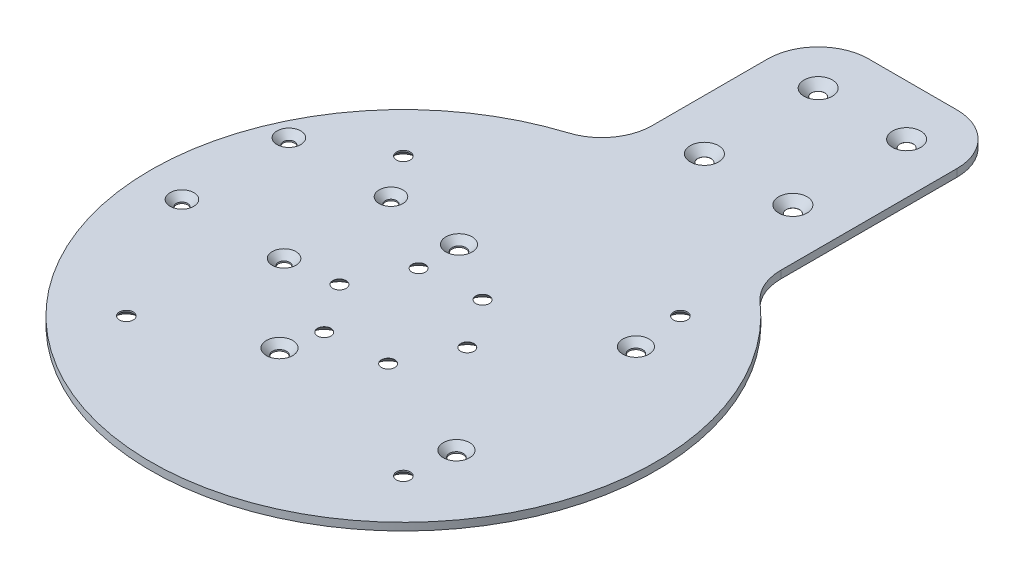
SolidWorks part; units mm, degrees
other "Markup1"
sketch "Sketch22" plane through (-100, 5, 100) normal (0, 1, 0) x (-1, 0, 0)
other "Markup2"
sketch "Sketch23" plane through (-100, 0, -180.1) normal (0, -1, 0) x (1, 0, 0)
material "6061-T6 (SS)"
ref_plane "Front Plane" through (0, 0, 0) normal (0, 0, 1) x (1, 0, 0)
ref_plane "Top Plane" through (0, 0, 0) normal (0, 1, 0) x (1, 0, 0)
ref_plane "Right Plane" through (0, 0, 0) normal (1, 0, 0) x (0, 0, -1)
sketch "Sketch1" plane through (0, 0, 0) normal (0, 1, 0) x (1, 0, 0)
  circle A0 centre (0, 0) radius 100
  dimension "D1" = 200
extrude "Boss-Extrude1" add sketch "Sketch1" along normal blind 3
sketch "Sketch2" plane through (0, 0, 0) normal (0, -1, 0) x (1, 0, 0)
  circle A0 centre (0, 0) radius 105
  dimension "D1" = 210
sketch "Sketch3" plane through (0, 0, 0) normal (0, 0, 1) x (1, 0, 0)
  line L1 (100, 3) -> (-100, 3) construction
  circle A0 centre (105, 4) radius 3.25
  dimension "D1" = 6.5
  dimension "D2" = 1
  dimension "D3" = 105
sweep "Cut-Sweep1" [suppressed] cut profiles "Sketch3" path "Sketch2"
sketch "Sketch4" plane through (0, 0, 0) normal (0, -1, 0) x (1, 0, 0)
  circle A0 centre (0, 0) radius 100 construction
  circle A1 centre (23.4262, -1.8614) radius 2.6
  circle A3 centre (10.1011, -21.2183) radius 2.6
  circle A5 centre (-13.3251, -19.357) radius 2.6
  circle A7 centre (-23.4262, 1.8614) radius 2.6
  circle A9 centre (-10.1011, 21.2183) radius 2.6
  circle A11 centre (0, 0) radius 95 construction
  circle A13 centre (0, 0) radius 110 construction
  circle A14 centre (0, 0) radius 29.5 construction
  circle A18 centre (13.3251, 19.357) radius 2.6
  point P14 (0, 0)
  dimension "D1" = 59
  dimension "D2" = 6
  dimension "D4" = 190
  dimension "D5" = 220
  dimension "D3" = 23.5
hole_wizard "CSK for M5 SFHCS1" positions "Sketch5" profile "Sketch6" countersink size "M5" standard "ANSI Metric" end condition through all
sketch "Sketch5" plane through (0, 0, 0) normal (0, -1, 0) x (-1, 0, 0)
  point P0 (13.3251, 19.357)
  point P3 (-10.1011, 21.2183)
  point P6 (-23.4262, 1.8614)
  point P9 (-13.3251, -19.357)
  point P12 (10.1011, -21.2183)
  point P15 (23.4262, -1.8614)
sketch "Sketch6" plane through (-13.3251, 0, -19.357) normal (1, 0, 0) x (0, 0, -1)
  line L0 (0, 0) -> (0, 3)
  line L1 (0, 3) -> (2.65, 3)
  line L2 (2.65, 3) -> (2.65, 2.95)
  line L3 (2.65, 2.95) -> (5.6, 0)
  line L5 (5.6, 0) -> (0, 0)
  line L6 (-2.65, 2.95) -> (-5.6, 0) construction
  line L11 (0, -6.35) -> (0, 107.95) construction
  dimension "Thru Hole Dia." = 5.3
  dimension "Thru Hole Depth" = 3
  dimension "Near C'Sink Dia." = 11.2
  dimension "Near C'Sink Angle" = 90
sketch "Sketch7" plane through (0, 0, 0) normal (0, -1, 0) x (1, 0, 0)
  line L4 (-16, -98.7117) -> (-16, -180.1)
  line L5 (-16, -180.1) -> (59, -180.1)
  line L6 (59, -180.1) -> (59, -80.7403)
  arc A0 (-16, -98.7117) -> (59, -80.7403) centre (0, 0) ccw
  circle A1 centre (0, 0) radius 110 construction
  circle A2 centre (0, 0) radius 100 construction
  dimension "D1" = 75
  dimension "D2" = 16
  dimension "D3" = 180.1
extrude "Boss-Extrude2" add sketch "Sketch7" against normal blind 3
fillet "Fillet1" radius 20 4 edges at (-16, 1.5, -180.1) (59, 1.5, -180.1) (59, 1.5, -80.7403) (-16, 1.5, -98.7117)
sketch "Sketch11" plane through (0, 3, 0) normal (0, -1, 0) x (1, 0, 0)
  line L0 (59, -160.1) -> (59, -90.3272) construction
  line L1 (4, -180.1) -> (39, -180.1) construction
  circle A0 centre (4, -115.1) radius 3.1
  circle A1 centre (39, -115.1) radius 3.1
  circle A2 centre (39, -160.1) radius 3.1
  circle A3 centre (4, -160.1) radius 3.1
  dimension "D1" = 6.2
  dimension "D2" = 6.2
  dimension "D3" = 6.2
  dimension "D4" = 6.2
  dimension "D5" = 35
  dimension "D6" = 45
  dimension "D7" = 20
  dimension "D8" = 20
hole_wizard "CSK for M5 SFHCS2" positions "Sketch12" profile "Sketch14" countersink size "M5" standard "ANSI Metric" end condition through all
sketch "Sketch12" plane through (0, 3, 0) normal (0, 1, 0) x (1, 0, 0)
  point P0 (39, 160.1)
  point P3 (4, 160.1)
  point P6 (39, 115.1)
  point P9 (4, 115.1)
sketch "Sketch14" plane through (39, 3, -160.1) normal (1, 0, 0) x (0, 0, 1)
  line L0 (0, 0) -> (0, 3)
  line L1 (0, 3) -> (2.65, 3)
  line L2 (2.65, 3) -> (2.65, 2.95)
  line L3 (2.65, 2.95) -> (5.6, 0)
  line L5 (5.6, 0) -> (0, 0)
  line L6 (-2.65, 2.95) -> (-5.6, 0) construction
  line L11 (0, -6.35) -> (0, 107.95) construction
  dimension "Thru Hole Dia." = 5.3
  dimension "Thru Hole Depth" = 3
  dimension "Near C'Sink Dia." = 11.2
  dimension "Near C'Sink Angle" = 90
sketch "Sketch15" plane through (0, 0, 0) normal (0, -1, 0) x (1, 0, 0)
  line L0 (0, 0) -> (-54.8008, 54.8008) construction
  line L1 (0, 77.5) -> (0, 0) construction
  circle A0 centre (56.5, -35.5) radius 2.5
  circle A1 centre (56.5, 35.5) radius 2.5
  circle A2 centre (-13.5, 35.5) radius 2.5
  circle A3 centre (-13.5, -35.5) radius 2.5
  circle A4 centre (-43.3, -38.4) radius 2
  circle A5 centre (-43.3, 3.9) radius 2
  circle A6 centre (-83.7, -38.4) radius 2
  circle A7 centre (-83.7, 3.9) radius 2
  circle A8 centre (0, 0) radius 70 construction
  arc A9 (65.8333, -75.2727) -> (-30, -95.3939) centre (0, 0) ccw construction
  circle A10 centre (0, 0) radius 77.5 construction
  circle A12 centre (-54.8008, 54.8008) radius 2.5
  circle A13 centre (54.8008, 54.8008) radius 2.5
  circle A14 centre (54.8008, -54.8008) radius 2.5
  circle A15 centre (-54.8008, -54.8008) radius 2.5
  point P35 (0, 0)
  dimension "D1" = 30
  dimension "D2" = 7.5
  dimension "D3" = 5
  dimension "D4" = 45
  dimension "D5" = 4
hole_wizard "CSK for M5 Flat Head Machine Screw2" positions "Sketch16" profile "Sketch17" countersink size "M5" standard "ANSI Metric" end condition through all
sketch "Sketch16" plane through (0, 3, 0) normal (0, 1, 0) x (1, 0, 0)
  circle A2 centre (-83.7, -3.9) radius 2
  circle A3 centre (-83.7, -3.9) radius 2
  circle A6 centre (-83.7, 38.4) radius 2
  circle A7 centre (-83.7, 38.4) radius 2
  circle A10 centre (-43.3, -3.9) radius 2
  circle A11 centre (-43.3, -3.9) radius 2
  circle A14 centre (-43.3, 38.4) radius 2
  circle A15 centre (-43.3, 38.4) radius 2
  circle A18 centre (-13.5, 35.5) radius 2.5
  circle A19 centre (-13.5, 35.5) radius 2.5
  circle A22 centre (-13.5, -35.5) radius 2.5
  circle A23 centre (-13.5, -35.5) radius 2.5
  circle A26 centre (56.5, -35.5) radius 2.5
  circle A27 centre (56.5, -35.5) radius 2.5
  circle A30 centre (56.5, 35.5) radius 2.5
  circle A31 centre (56.5, 35.5) radius 2.5
  point P33 (-13.5, 35.5)
  point P40 (-13.5, -35.5)
  point P47 (56.5, -35.5)
  point P54 (56.5, 35.5)
  dimension "D1" = 0
  dimension "D2" = 0
  dimension "D3" = 0
  dimension "D4" = 0
  dimension "D5" = 0
  dimension "D6" = 0
  dimension "D7" = 0
  dimension "D8" = 0
sketch "Sketch17" plane through (56.5, 3, -35.5) normal (1, 0, 0) x (0, 0, 1)
  line L0 (0, 0) -> (0, 3)
  line L1 (0, 3) -> (2.75, 3)
  line L2 (2.75, 3) -> (2.75, 2.45)
  line L3 (2.75, 2.45) -> (5.2, 0)
  line L5 (5.2, 0) -> (0, 0)
  line L6 (-2.75, 2.45) -> (-5.2, 0) construction
  line L11 (0, -6.35) -> (0, 107.95) construction
  dimension "Thru Hole Dia." = 5.5
  dimension "Thru Hole Depth" = 3
  dimension "Near C'Sink Dia." = 10.4
  dimension "Near C'Sink Angle" = 90
sketch "Sketch18" plane through (0, 3, 0) normal (0, 1, 0) x (1, 0, 0)
  point P0 (-43.3, 38.4)
  point P3 (-43.3, -3.9)
  point P6 (-83.7, 38.4)
  point P9 (-83.7, -3.9)
hole_wizard "CSK for M4 Flat Head Machine Screw1" positions "Sketch18" profile "Sketch19" countersink size "M4" standard "ANSI Metric" end condition through all
sketch "Sketch19" plane through (-43.3, 3, -38.4) normal (1, 0, 0) x (0, 0, 1)
  line L0 (0, 0) -> (0, 3)
  line L1 (0, 3) -> (2.25, 3)
  line L2 (2.25, 3) -> (2.25, 2.45)
  line L3 (2.25, 2.45) -> (4.7, 0)
  line L5 (4.7, 0) -> (0, 0)
  line L6 (-2.25, 2.45) -> (-4.7, 0) construction
  line L11 (0, -6.35) -> (0, 107.95) construction
  dimension "Thru Hole Dia." = 4.5
  dimension "Thru Hole Depth" = 3
  dimension "Near C'Sink Dia." = 9.4
  dimension "Near C'Sink Angle" = 90
sketch "Sketch20" plane through (0, 0, 0) normal (0, -1, 0) x (-1, 0, 0)
  point P0 (54.8008, -54.8008)
  point P3 (-54.8008, 54.8008)
  point P6 (54.8008, 54.8008)
  point P9 (-54.8008, -54.8008)
hole_wizard "CSK for M5 Flat Head Machine Screw3" positions "Sketch20" profile "Sketch21" countersink size "M5" standard "ANSI Metric" end condition through all
sketch "Sketch21" plane through (-54.8008, 0, 54.8008) normal (1, 0, 0) x (0, 0, -1)
  line L0 (0, 0) -> (0, 3)
  line L1 (0, 3) -> (2.75, 3)
  line L2 (2.75, 3) -> (2.75, 2.45)
  line L3 (2.75, 2.45) -> (5.2, 0)
  line L5 (5.2, 0) -> (0, 0)
  line L6 (-2.75, 2.45) -> (-5.2, 0) construction
  line L11 (0, -6.35) -> (0, 107.95) construction
  dimension "Thru Hole Dia." = 5.5
  dimension "Thru Hole Depth" = 3
  dimension "Near C'Sink Dia." = 10.4
  dimension "Near C'Sink Angle" = 90
